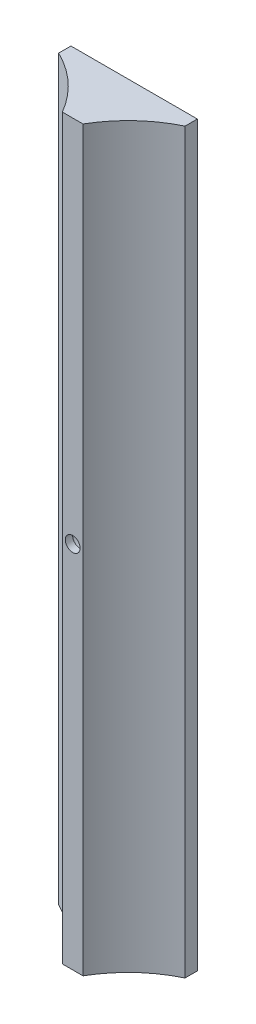
SolidWorks part; units mm, degrees
material "6061-T6 (SS)"
ref_plane "Front" through (0, 0, 0) normal (0, 0, 1) x (1, 0, 0)
ref_plane "Top" through (0, 0, 0) normal (0, 1, 0) x (1, 0, 0)
ref_plane "Right" through (0, 0, 0) normal (1, 0, 0) x (0, 0, -1)
sketch "Sketch1" plane through (0, 0, 0) normal (0, 1, 0) x (1, 0, 0)
  line L0 (-0.8397, 0) -> (0.8397, 0)
  line L1 (5.1411, 4) -> (5.1411, 5)
  line L2 (5.1411, 5) -> (-5.1411, 5)
  line L3 (-5.1411, 5) -> (-5.1411, 4)
  arc A0 (0.8397, 0) -> (5.1411, 4) centre (9.5, -5) cw
  arc A1 (-5.1411, 4) -> (-0.8397, 0) centre (-9.5, -5) cw
  point P9 (0, 5)
  point P10 (0, 0)
  dimension "D1" = 10
  dimension "D6" = 5
  dimension "D2" = 19
  dimension "D3" = 10
  dimension "D4" = 1
extrude "Boss-Extrude1" add sketch "Sketch1" along normal mid plane 60
sketch "Sketch3" plane through (0, 0, -5) normal (0, 0, -1) x (-1, 0, 0)
  line L0 (0, -30) -> (0, 30) construction
  line L1 (-5.1411, -30) -> (5.1411, -30) construction
  line L2 (-5.1411, 30) -> (5.1411, 30) construction
  point P6 (0, 0)
  dimension "D2" = 30
hole_wizard "Tapped Hole for M2.5x0.45 Helicoil1" positions "3DSketch1" profile "Sketch4" tap size "M2.5x0.45" standard "Helicoil® Metric"
sketch3d "3DSketch1"
  point P0 (0, 0, -5)
cosmetic thread "Hole Thread2" parameters "D1"=3, "D2"=3.145
sketch "Sketch4" plane through (0, 0, -5) normal (1, 0, 0) x (0, 1, 0)
  line L0 (0, 0) -> (0, 4.7661)
  line L1 (0, 4.7661) -> (1.275, 4)
  line L2 (1.275, 4) -> (1.275, 0)
  line L5 (1.275, 0) -> (0, 0)
  line L10 (0, 4.7661) -> (-1.275, 4) construction
  line L11 (0, -6.35) -> (0, 107.95) construction
  dimension "Tap Drill Dia." = 2.55
  dimension "Tap Drill Depth" = 4
  dimension "Drill Angle" = 118
hole_wizard "Ø1.2 (1.2) Diameter Hole1" positions "3DSketch2" profile "Sketch5" hole size "Ø1.2" standard "ANSI Metric"
sketch3d "3DSketch2"
  point P0 (0, 0, -5)
sketch "Sketch5" plane through (0, 0, -5) normal (1, 0, 0) x (0, 1, 0)
  line L0 (0, 0) -> (0, 6.8105)
  line L1 (0, 6.8105) -> (0.6, 6.45)
  line L2 (0.6, 6.45) -> (0.6, 0)
  line L5 (0.6, 0) -> (0, 0)
  line L10 (0, 6.8105) -> (-0.6, 6.45) construction
  line L11 (0, -6.35) -> (0, 107.95) construction
  dimension "Hole Dia." = 1.2
  dimension "Hole Depth" = 6.45
  dimension "Drill Angle" = 118
